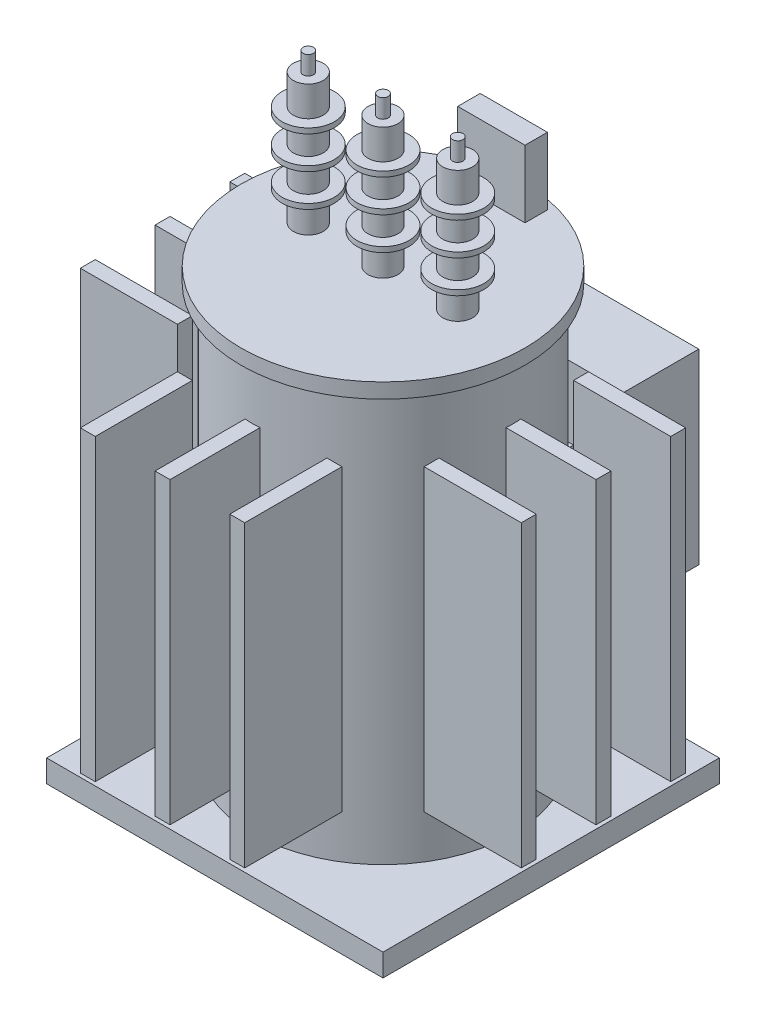
SolidWorks part; units mm, degrees
ref_plane "Front Plane" through (0, 0, 0) normal (0, 0, 1) x (1, 0, 0)
ref_plane "Top Plane" through (0, 0, 0) normal (0, 1, 0) x (1, 0, 0)
ref_plane "Right Plane" through (0, 0, 0) normal (1, 0, 0) x (0, 0, -1)
sketch "Sketch1" plane through (0, 0, 0) normal (0, 1, 0) x (1, 0, 0)
  line L1 (-450, -450) -> (450, -450)
  line L2 (-450, -450) -> (-450, 450)
  line L3 (-450, 450) -> (450, 450)
  line L4 (450, -450) -> (450, 450)
  line L5 (-450, -450) -> (450, 450) construction
  line L6 (-450, 450) -> (450, -450) construction
  point P0 (0, 0)
extrude "Base" add sketch "Sketch1" along normal blind 60 separate body
sketch "Sketch2" plane through (0, 0, 0) normal (0, 1, 0) x (1, 0, 0)
  circle A0 centre (0, 0) radius 350
extrude "Tank" add sketch "Sketch2" along normal blind 1100 from offset 60 separate body
sketch "Sketch3" plane through (0, 0, 0) normal (0, 1, 0) x (1, 0, 0)
  circle A0 centre (0, 0) radius 380
extrude "Lid" add sketch "Sketch3" along normal blind 40 from offset 1160 separate body
sketch "Sketch4" plane through (0, 0, 0) normal (0, 1, 0) x (1, 0, 0)
  line L1 (330, 180) -> (590, 180)
  line L2 (330, 180) -> (330, 220)
  line L3 (330, 220) -> (590, 220)
  line L4 (590, 180) -> (590, 220)
  line L5 (330, 180) -> (590, 220) construction
  line L6 (330, 220) -> (590, 180) construction
  point P0 (460, 200)
extrude "Fin +x 1" add sketch "Sketch4" along normal blind 800 from offset 210 separate body
sketch "Sketch5" plane through (0, 0, 0) normal (0, 1, 0) x (1, 0, 0)
  line L1 (-590, 180) -> (-330, 180)
  line L2 (-590, 180) -> (-590, 220)
  line L3 (-590, 220) -> (-330, 220)
  line L4 (-330, 180) -> (-330, 220)
  line L5 (-590, 180) -> (-330, 220) construction
  line L6 (-590, 220) -> (-330, 180) construction
  point P0 (-460, 200)
extrude "Fin -x 1" add sketch "Sketch5" along normal blind 800 from offset 210 separate body
sketch "Sketch6" plane through (0, 0, 0) normal (0, 1, 0) x (1, 0, 0)
  line L1 (-220, -590) -> (-180, -590)
  line L2 (-220, -590) -> (-220, -330)
  line L3 (-220, -330) -> (-180, -330)
  line L4 (-180, -590) -> (-180, -330)
  line L5 (-220, -590) -> (-180, -330) construction
  line L6 (-220, -330) -> (-180, -590) construction
  point P0 (-200, -460)
extrude "Fin +z 1" add sketch "Sketch6" along normal blind 800 from offset 210 separate body
sketch "Sketch7" plane through (0, 0, 0) normal (0, 1, 0) x (1, 0, 0)
  line L1 (330, -20) -> (590, -20)
  line L2 (330, -20) -> (330, 20)
  line L3 (330, 20) -> (590, 20)
  line L4 (590, -20) -> (590, 20)
  line L5 (330, -20) -> (590, 20) construction
  line L6 (330, 20) -> (590, -20) construction
  point P0 (460, 0)
extrude "Fin +x 2" add sketch "Sketch7" along normal blind 800 from offset 210 separate body
sketch "Sketch8" plane through (0, 0, 0) normal (0, 1, 0) x (1, 0, 0)
  line L1 (-590, -20) -> (-330, -20)
  line L2 (-590, -20) -> (-590, 20)
  line L3 (-590, 20) -> (-330, 20)
  line L4 (-330, -20) -> (-330, 20)
  line L5 (-590, -20) -> (-330, 20) construction
  line L6 (-590, 20) -> (-330, -20) construction
  point P0 (-460, 0)
extrude "Fin -x 2" add sketch "Sketch8" along normal blind 800 from offset 210 separate body
sketch "Sketch9" plane through (0, 0, 0) normal (0, 1, 0) x (1, 0, 0)
  line L1 (-20, -590) -> (20, -590)
  line L2 (-20, -590) -> (-20, -330)
  line L3 (-20, -330) -> (20, -330)
  line L4 (20, -590) -> (20, -330)
  line L5 (-20, -590) -> (20, -330) construction
  line L6 (-20, -330) -> (20, -590) construction
  point P0 (0, -460)
extrude "Fin +z 2" add sketch "Sketch9" along normal blind 800 from offset 210 separate body
sketch "Sketch10" plane through (0, 0, 0) normal (0, 1, 0) x (1, 0, 0)
  line L1 (330, -220) -> (590, -220)
  line L2 (330, -220) -> (330, -180)
  line L3 (330, -180) -> (590, -180)
  line L4 (590, -220) -> (590, -180)
  line L5 (330, -220) -> (590, -180) construction
  line L6 (330, -180) -> (590, -220) construction
  point P0 (460, -200)
extrude "Fin +x 3" add sketch "Sketch10" along normal blind 800 from offset 210 separate body
sketch "Sketch11" plane through (0, 0, 0) normal (0, 1, 0) x (1, 0, 0)
  line L1 (-590, -220) -> (-330, -220)
  line L2 (-590, -220) -> (-590, -180)
  line L3 (-590, -180) -> (-330, -180)
  line L4 (-330, -220) -> (-330, -180)
  line L5 (-590, -220) -> (-330, -180) construction
  line L6 (-590, -180) -> (-330, -220) construction
  point P0 (-460, -200)
extrude "Fin -x 3" add sketch "Sketch11" along normal blind 800 from offset 210 separate body
sketch "Sketch12" plane through (0, 0, 0) normal (0, 1, 0) x (1, 0, 0)
  line L1 (180, -590) -> (220, -590)
  line L2 (180, -590) -> (180, -330)
  line L3 (180, -330) -> (220, -330)
  line L4 (220, -590) -> (220, -330)
  line L5 (180, -590) -> (220, -330) construction
  line L6 (180, -330) -> (220, -590) construction
  point P0 (200, -460)
extrude "Fin +z 3" add sketch "Sketch12" along normal blind 800 from offset 210 separate body
sketch "Sketch13" plane through (0, 0, 0) normal (0, 1, 0) x (1, 0, 0)
  circle A0 centre (-200, 0) radius 40
extrude "Bushing S" add sketch "Sketch13" along normal blind 350 from offset 1200 separate body
sketch "Sketch14" plane through (0, 0, 0) normal (0, 1, 0) x (1, 0, 0)
  circle A0 centre (-200, 0) radius 70
extrude "Shed S 1" add sketch "Sketch14" along normal blind 14 from offset 1280.5 separate body
sketch "Sketch15" plane through (0, 0, 0) normal (0, 1, 0) x (1, 0, 0)
  circle A0 centre (-200, 0) radius 70
extrude "Shed S 2" add sketch "Sketch15" along normal blind 14 from offset 1368 separate body
sketch "Sketch16" plane through (0, 0, 0) normal (0, 1, 0) x (1, 0, 0)
  circle A0 centre (-200, 0) radius 70
extrude "Shed S 3" add sketch "Sketch16" along normal blind 14 from offset 1455.5 separate body
sketch "Sketch17" plane through (0, 0, 0) normal (0, 1, 0) x (1, 0, 0)
  circle A0 centre (-200, 0) radius 14
extrude "Terminal S" add sketch "Sketch17" along normal blind 50 from offset 1550 separate body
sketch "Sketch18" plane through (0, 0, 0) normal (0, 1, 0) x (1, 0, 0)
  circle A0 centre (0, 0) radius 40
extrude "Bushing L" add sketch "Sketch18" along normal blind 350 from offset 1200 separate body
sketch "Sketch19" plane through (0, 0, 0) normal (0, 1, 0) x (1, 0, 0)
  circle A0 centre (0, 0) radius 70
extrude "Shed L 1" add sketch "Sketch19" along normal blind 14 from offset 1280.5 separate body
sketch "Sketch20" plane through (0, 0, 0) normal (0, 1, 0) x (1, 0, 0)
  circle A0 centre (0, 0) radius 70
extrude "Shed L 2" add sketch "Sketch20" along normal blind 14 from offset 1368 separate body
sketch "Sketch21" plane through (0, 0, 0) normal (0, 1, 0) x (1, 0, 0)
  circle A0 centre (0, 0) radius 70
extrude "Shed L 3" add sketch "Sketch21" along normal blind 14 from offset 1455.5 separate body
sketch "Sketch22" plane through (0, 0, 0) normal (0, 1, 0) x (1, 0, 0)
  circle A0 centre (0, 0) radius 14
extrude "Terminal L" add sketch "Sketch22" along normal blind 50 from offset 1550 separate body
sketch "Sketch23" plane through (0, 0, 0) normal (0, 1, 0) x (1, 0, 0)
  circle A0 centre (200, 0) radius 40
extrude "Bushing SL" add sketch "Sketch23" along normal blind 350 from offset 1200 separate body
sketch "Sketch24" plane through (0, 0, 0) normal (0, 1, 0) x (1, 0, 0)
  circle A0 centre (200, 0) radius 70
extrude "Shed SL 1" add sketch "Sketch24" along normal blind 14 from offset 1280.5 separate body
sketch "Sketch25" plane through (0, 0, 0) normal (0, 1, 0) x (1, 0, 0)
  circle A0 centre (200, 0) radius 70
extrude "Shed SL 2" add sketch "Sketch25" along normal blind 14 from offset 1368 separate body
sketch "Sketch26" plane through (0, 0, 0) normal (0, 1, 0) x (1, 0, 0)
  circle A0 centre (200, 0) radius 70
extrude "Shed SL 3" add sketch "Sketch26" along normal blind 14 from offset 1455.5 separate body
sketch "Sketch27" plane through (0, 0, 0) normal (0, 1, 0) x (1, 0, 0)
  circle A0 centre (200, 0) radius 14
extrude "Terminal SL" add sketch "Sketch27" along normal blind 50 from offset 1550 separate body
sketch "Sketch28" plane through (0, 0, 0) normal (0, 1, 0) x (1, 0, 0)
  line L1 (-90, 290) -> (90, 290)
  line L2 (-90, 290) -> (-90, 350)
  line L3 (-90, 350) -> (90, 350)
  line L4 (90, 290) -> (90, 350)
  line L5 (-90, 290) -> (90, 350) construction
  line L6 (-90, 350) -> (90, 290) construction
  point P0 (0, 320)
extrude "Position indicator" add sketch "Sketch28" along normal blind 180 from offset 1200 separate body
sketch "Sketch29" plane through (0, 0, 0) normal (0, 1, 0) x (1, 0, 0)
  line L1 (-175, 470) -> (175, 470)
  line L2 (-175, 470) -> (-175, 670)
  line L3 (-175, 670) -> (175, 670)
  line L4 (175, 470) -> (175, 670)
  line L5 (-175, 470) -> (175, 670) construction
  line L6 (-175, 670) -> (175, 470) construction
  point P0 (0, 570)
extrude "Control cabinet" add sketch "Sketch29" along normal blind 500 from offset 260 separate body
sketch "Sketch30" plane through (0, 0, 0) normal (0, 1, 0) x (1, 0, 0)
  line L1 (-40, 340) -> (40, 340)
  line L2 (-40, 340) -> (-40, 480)
  line L3 (-40, 480) -> (40, 480)
  line L4 (40, 340) -> (40, 480)
  line L5 (-40, 340) -> (40, 480) construction
  line L6 (-40, 480) -> (40, 340) construction
  point P0 (0, 410)
extrude "Cabinet bracket" add sketch "Sketch30" along normal blind 60 from offset 510 separate body
